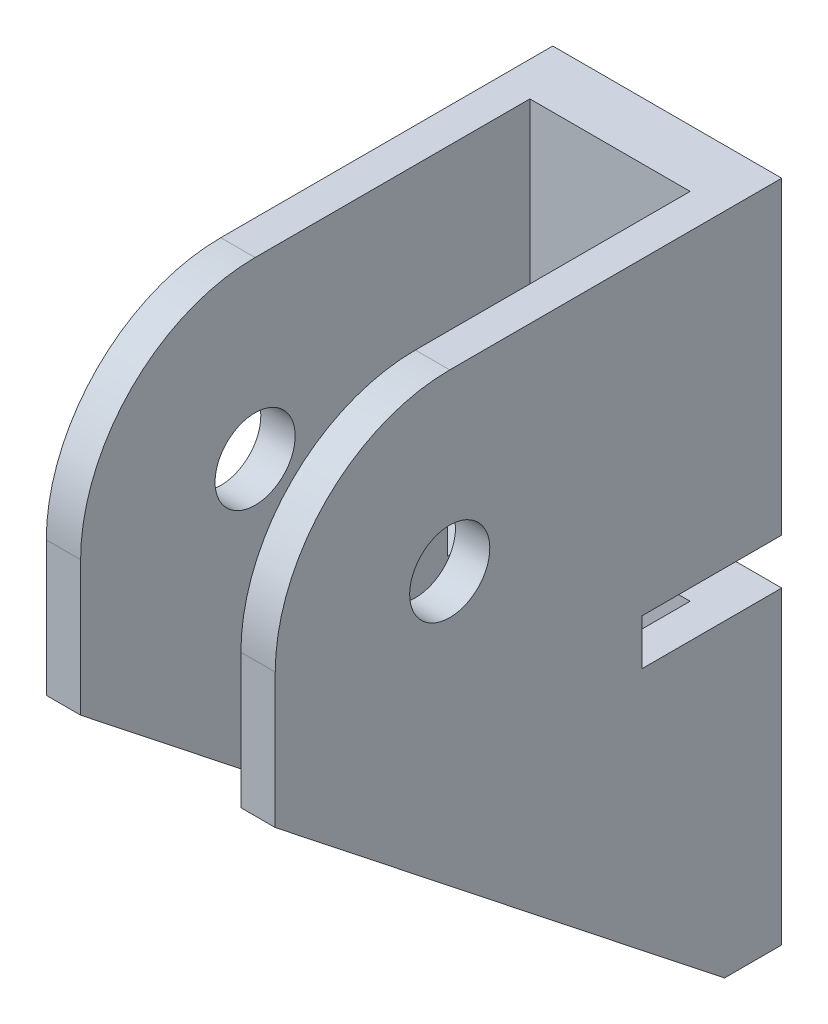
SolidWorks part; units mm, degrees
ref_plane "Front Plane" through (0, 0, 0) normal (0, 0, 1) x (1, 0, 0)
ref_plane "Top Plane" through (0, 0, 0) normal (0, 1, 0) x (1, 0, 0)
ref_plane "Right Plane" through (0, 0, 0) normal (1, 0, 0) x (0, 0, -1)
sketch "Sketch1" plane through (0, 0, 0) normal (0, 0, 1) x (1, 0, 0)
  line L0 (8.6306, 74.4219) -> (8.6306, 81.4219)
  line L3 (3.6306, 81.4219) -> (13.6306, 81.4219)
  line L4 (3.6306, 81.4219) -> (3.6306, 67.9219)
  line L5 (3.6306, 67.9219) -> (13.6306, 67.9219)
  line L6 (13.6306, 81.4219) -> (13.6306, 67.9219)
  line L8 (3.6306, 65.9219) -> (13.6306, 65.9219)
  line L9 (3.6306, 65.9219) -> (3.6306, 52.4219)
  line L10 (3.6306, 52.4219) -> (13.6306, 52.4219)
  line L11 (13.6306, 65.9219) -> (13.6306, 52.4219)
  circle A0 centre (8.6306, 59.9219) radius 1.75
  circle A1 centre (8.6306, 74.4219) radius 1.75
  dimension "D6" = 3.5
  dimension "D1" = 10
  dimension "D2" = 5
  dimension "D3" = 10
  dimension "D4" = 0
  dimension "D5" = 6
extrude "Boss-Extrude1" add sketch "Sketch1" along normal blind 2.5
sketch "Sketch2" plane through (3.6306, 0, 0) normal (-1, 0, 0) x (0, 0, 1)
  line L0 (2.5, 65.9219) -> (6.1002, 65.9219)
  line L1 (2.5, 81.4219) -> (14.5, 81.4219)
  line L2 (2.5, 81.4219) -> (2.5, 67.9219)
  line L3 (2.5, 67.9219) -> (22.12, 67.9219)
  line L4 (22.12, 73.8019) -> (22.12, 67.9219)
  line L5 (6.1002, 65.9219) -> (6.1002, 67.9219)
  line L6 (2.5, 52.4219) -> (22.12, 67.9219)
  line L7 (2.5, 52.4219) -> (2.5, 65.9219)
  circle A0 centre (17.5, -8.6887) radius 1.75
  arc A1 (14.5, 81.4219) -> (22.12, 73.8019) centre (14.5, 73.8019) cw
  line M9 (2.5, 67.9219) -> (2.5, 81.4219)
  dimension "D1" = 7.62
  dimension "D2" = 3.5
  dimension "D3" = 15
  dimension "D4" = 12
extrude "Boss-Extrude2" add sketch "Sketch2" against normal blind 1.5 contours A1 L1 L3 L4 A0 M9 | L7 L6 L3 L5 L0
sketch "Sketch4" plane through (0, 0, 2.5) normal (0, 0, 1) x (1, 0, 0)
  point P0 (8.6306, 74.4219)
  point P1 (9.388, 67.1193)
ref_plane "Plane2" through (8.6306, 0, 0) normal (-1, 0, 0) x (0, 0, 1)
mirror "Mirror1" about plane through (8.6306, 0, 0) normal (-1, 0, 0) of "Boss-Extrude2"
sketch "Sketch5" plane through (3.6306, 0, 0) normal (-1, 0, 0) x (0, 0, 1)
  line L0 (22.12, 73.8019) -> (14.5, 73.8019)
  circle A0 centre (14.5, 73.8019) radius 1.75
  dimension "D1" = 3.5
extrude "Cut-Extrude1" cut sketch "Sketch5" against normal blind 12.446
